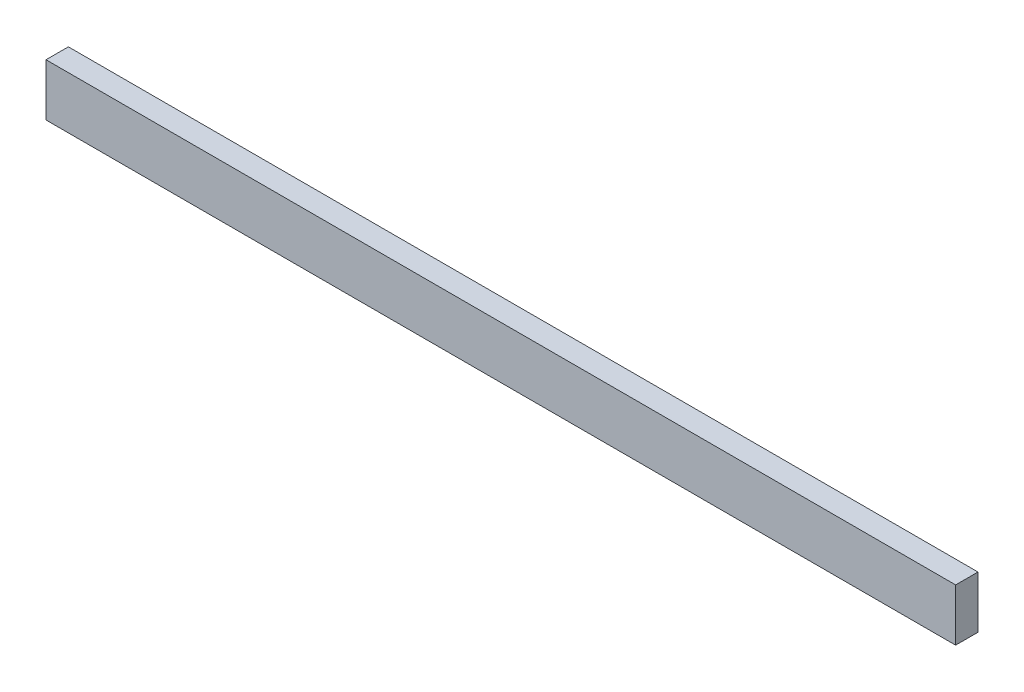
SolidWorks part; units mm, degrees
ref_plane "Front Plane" through (0, 0, 0) normal (0, 0, 1) x (1, 0, 0)
ref_plane "Top Plane" through (0, 0, 0) normal (0, 1, 0) x (1, 0, 0)
ref_plane "Right Plane" through (0, 0, 0) normal (1, 0, 0) x (0, 0, -1)
sketch "Sketch1" plane through (0, 0, 0) normal (0, 0, 1) x (1, 0, 0)
  line L1 (0, 0) -> (774.7, 0)
  line L2 (0, 0) -> (0, 44.45)
  line L3 (0, 44.45) -> (774.7, 44.45)
  line L4 (774.7, 0) -> (774.7, 44.45)
  dimension "D1" = 774.7
  dimension "D2" = 44.45
extrude "Boss-Extrude1" add sketch "Sketch1" along normal blind 19.05
